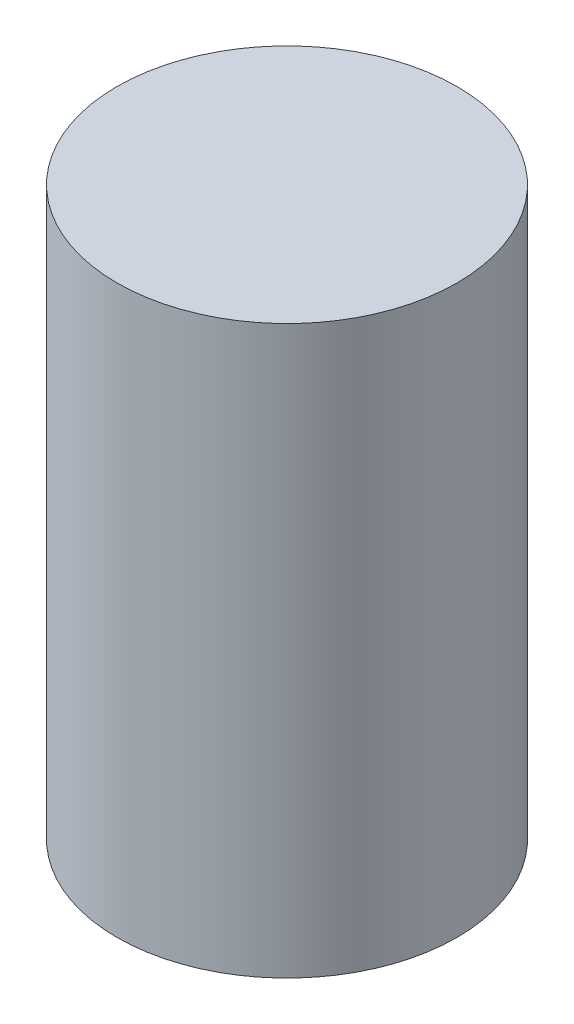
SolidWorks part; units mm, degrees
ref_plane "Front Plane" through (0, 0, 0) normal (0, 0, 1) x (1, 0, 0)
ref_plane "Top Plane" through (0, 0, 0) normal (0, 1, 0) x (1, 0, 0)
ref_plane "Right Plane" through (0, 0, 0) normal (1, 0, 0) x (0, 0, -1)
sketch "Sketch1" plane through (0, 0, 0) normal (0, 1, 0) x (1, 0, 0)
  circle A0 centre (0, 0) radius 1.5
  dimension "D1" = 3
extrude "Boss-Extrude1" add sketch "Sketch1" along normal blind 5
